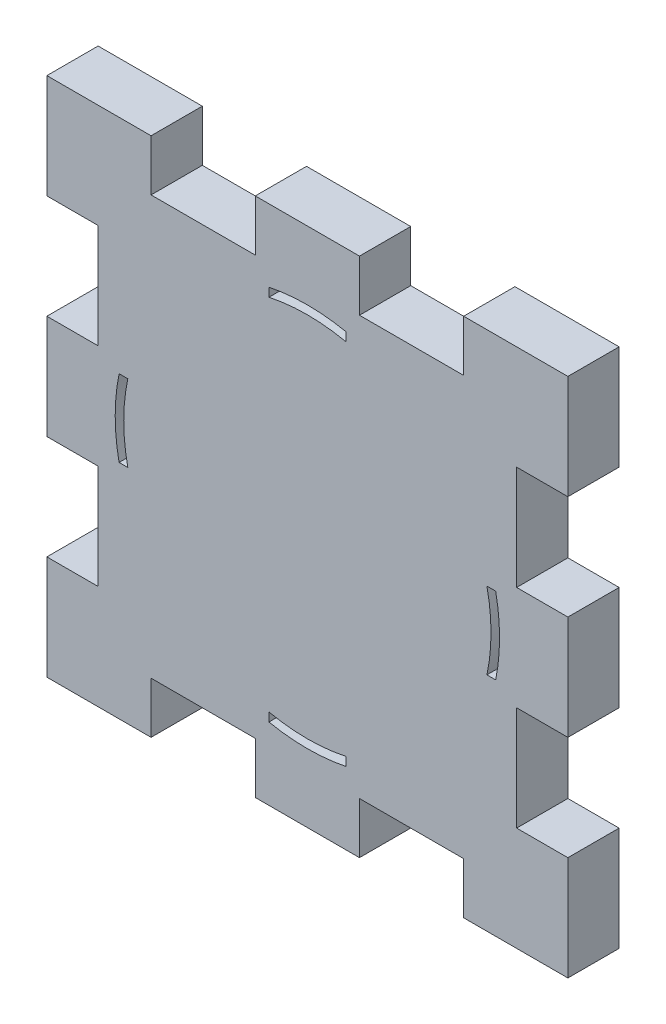
SolidWorks part; units mm, degrees
ref_plane "Front Plane" through (0, 0, 0) normal (0, 0, 1) x (1, 0, 0)
ref_plane "Top Plane" through (0, 0, 0) normal (0, 1, 0) x (1, 0, 0)
ref_plane "Right Plane" through (0, 0, 0) normal (1, 0, 0) x (0, 0, -1)
sketch "Sketch1" plane through (0, 0, 0) normal (0, 0, 1) x (1, 0, 0)
  line L1 (0, 0) -> (154.94, 0)
  line L2 (0, 0) -> (0, 154.94)
  line L3 (0, 154.94) -> (154.94, 154.94)
  line L4 (154.94, 0) -> (154.94, 154.94)
  dimension "D1" = 154.94
  dimension "D2" = 154.94
extrude "Boss-Extrude1" add sketch "Sketch1" along normal blind 15.24 contours L3 L4 L1 L2
sketch "Sketch3" plane through (0, 0, 15.24) normal (0, 0, 1) x (1, 0, 0)
  line L0 (0, 0) -> (0, 154.94) construction
  line L1 (0, 123.952) -> (15.24, 123.952)
  line L2 (0, 123.952) -> (0, 92.964)
  line L3 (0, 92.964) -> (15.24, 92.964)
  line L4 (15.24, 123.952) -> (15.24, 92.964)
  line L5 (154.94, 0) -> (154.94, 154.94) construction
  line L6 (0, 61.976) -> (15.24, 61.976)
  line L7 (0, 61.976) -> (0, 30.988)
  line L8 (0, 30.988) -> (15.24, 30.988)
  line L9 (15.24, 61.976) -> (15.24, 30.988)
  line L10 (154.94, 123.952) -> (139.7, 123.952)
  line L11 (154.94, 123.952) -> (154.94, 92.964)
  line L12 (154.94, 92.964) -> (139.7, 92.964)
  line L13 (139.7, 123.952) -> (139.7, 92.964)
  line L14 (15.24, 123.952) -> (15.24, 154.94) construction
  line L15 (154.94, 61.976) -> (139.7, 61.976)
  line L16 (154.94, 61.976) -> (154.94, 30.988)
  line L17 (154.94, 30.988) -> (139.7, 30.988)
  line L18 (139.7, 61.976) -> (139.7, 30.988)
  line L19 (0, 154.94) -> (154.94, 154.94) construction
  line L20 (15.24, 92.964) -> (15.24, 61.976) construction
  line L21 (15.24, 30.988) -> (15.24, 0) construction
  line L22 (0, 0) -> (154.94, 0) construction
  line L23 (139.7, 123.952) -> (139.7, 154.94) construction
  line L24 (139.7, 92.964) -> (139.7, 61.976) construction
  line L25 (139.7, 30.988) -> (139.7, 0) construction
  line L26 (30.988, 139.7) -> (0, 139.7) construction
  line L27 (30.988, 154.94) -> (61.976, 154.94)
  line L28 (30.988, 154.94) -> (30.988, 139.7)
  line L29 (30.988, 139.7) -> (61.976, 139.7)
  line L30 (61.976, 154.94) -> (61.976, 139.7)
  line L31 (92.964, 154.94) -> (123.952, 154.94)
  line L32 (92.964, 154.94) -> (92.964, 139.7)
  line L33 (92.964, 139.7) -> (123.952, 139.7)
  line L34 (123.952, 154.94) -> (123.952, 139.7)
  line L35 (30.988, 0) -> (61.976, 0)
  line L36 (30.988, 0) -> (30.988, 15.24)
  line L37 (30.988, 15.24) -> (61.976, 15.24)
  line L38 (61.976, 0) -> (61.976, 15.24)
  line L39 (92.964, 0) -> (123.952, 0)
  line L40 (92.964, 0) -> (92.964, 15.24)
  line L41 (92.964, 15.24) -> (123.952, 15.24)
  line L42 (123.952, 0) -> (123.952, 15.24)
  line L43 (61.976, 139.7) -> (92.964, 139.7) construction
  line L44 (123.952, 139.7) -> (154.94, 139.7) construction
  line L45 (30.988, 15.24) -> (0, 15.24) construction
  line L46 (61.976, 15.24) -> (92.964, 15.24) construction
  line L47 (123.952, 15.24) -> (154.94, 15.24) construction
  dimension "D1" = 15.24
  dimension "D2" = 15.24
  dimension "D3" = 15.24
  dimension "D4" = 15.24
extrude "Cut-Extrude1" cut sketch "Sketch3" against normal through all
sketch "Sketch7" plane through (0, 0, 15.24) normal (0, 0, 1) x (1, 0, 0)
  line L0 (0, 77.47) -> (154.94, 77.47) construction
  line L3 (0, 61.976) -> (0, 92.964) construction
  line L6 (154.94, 61.976) -> (154.94, 92.964) construction
  line L7 (77.47, 154.94) -> (77.47, 0) construction
  line L8 (61.976, 154.94) -> (92.964, 154.94) construction
  line L9 (61.976, 0) -> (92.964, 0) construction
  line L10 (21.4747, 66.04) -> (24.0696, 66.04)
  line L12 (21.4747, 88.9) -> (24.0696, 88.9)
  line L14 (88.9, 24.0696) -> (88.9, 21.4747)
  line L15 (66.04, 24.0696) -> (66.04, 21.4747)
  line L16 (130.8704, 88.9) -> (133.4653, 88.9)
  line L17 (130.8704, 66.04) -> (133.4653, 66.04)
  line L18 (88.9, 133.4653) -> (88.9, 130.8704)
  line L19 (66.04, 133.4653) -> (66.04, 130.8704)
  circle A0 centre (77.47, 77.47) radius 57.15 construction
  circle A1 centre (77.47, 77.47) radius 54.61 construction
  arc A2 (24.0696, 88.9) -> (24.0696, 66.04) centre (77.47, 77.47) ccw
  arc A4 (21.4747, 88.9) -> (21.4747, 66.04) centre (77.47, 77.47) ccw
  arc A5 (66.04, 24.0696) -> (88.9, 24.0696) centre (77.47, 77.47) ccw
  arc A6 (66.04, 21.4747) -> (88.9, 21.4747) centre (77.47, 77.47) ccw
  arc A7 (130.8704, 66.04) -> (130.8704, 88.9) centre (77.47, 77.47) ccw
  arc A8 (133.4653, 66.04) -> (133.4653, 88.9) centre (77.47, 77.47) ccw
  arc A10 (66.04, 130.8704) -> (88.9, 130.8704) centre (77.47, 77.47) cw
  arc A11 (66.04, 133.4653) -> (88.9, 133.4653) centre (77.47, 77.47) cw
  point P31 (0, 0)
  point P32 (0, 0)
  point P33 (0, 0)
  point P34 (0, 0)
  point P35 (0, 0)
  point P36 (0, 0)
  point P37 (0, 0)
  point P38 (0, 0)
  point P39 (0, 0)
  point P40 (0, 0)
  point P41 (0, 0)
  point P42 (0, 0)
  point P43 (0, 0)
  point P44 (0, 0)
  point P45 (0, 0)
  point P46 (0, 0)
  point P47 (0, 0)
  dimension "D1" = 114.3
  dimension "D2" = 2.54
  dimension "D3" = 11.43
  dimension "D4" = 22.86
  dimension "D5" = 11.43
  dimension "D6" = 22.86
  dimension "D7" = 11.43
  dimension "D8" = 11.43
  dimension "D9" = 22.86
  dimension "D10" = 22.86
  dimension "D11" = 11.43
  dimension "D12" = 11.43
  dimension "D13" = 22.86
  dimension "D14" = 22.86
  dimension "D15" = 11.43
  dimension "D16" = 11.43
  dimension "D17" = 22.86
  dimension "D18" = 22.86
extrude "Cut-Extrude2" cut sketch "Sketch7" against normal through all contours A6 L14 A5 L15 | A8 L16 A7 L17 | A4 L10 A2 L12 | A11 L18 A10 L19
equation "\"MDF\"= .3"
equation "\"Foamcore\"= .1"
equation "\"GMaterial\"= .6"
equation "\"CutDistance\" = .1"
equation "\"D1@Boss-Extrude1\"=\"GMaterial\""
equation "\"D1@Sketch1\"=\"GMaterial\"+5.5"
equation "\"D2@Sketch1\"=\"GMaterial\"  + 5.5"
equation "\"D1@Sketch3\"=\"GMaterial\""
equation "\"D2@Sketch3\"=\"GMaterial\""
equation "\"D3@Sketch3\"=\"GMaterial\""
equation "\"D4@Sketch3\"=\"GMaterial\""
equation "\"D2@Sketch7\"=\"Foamcore\""
